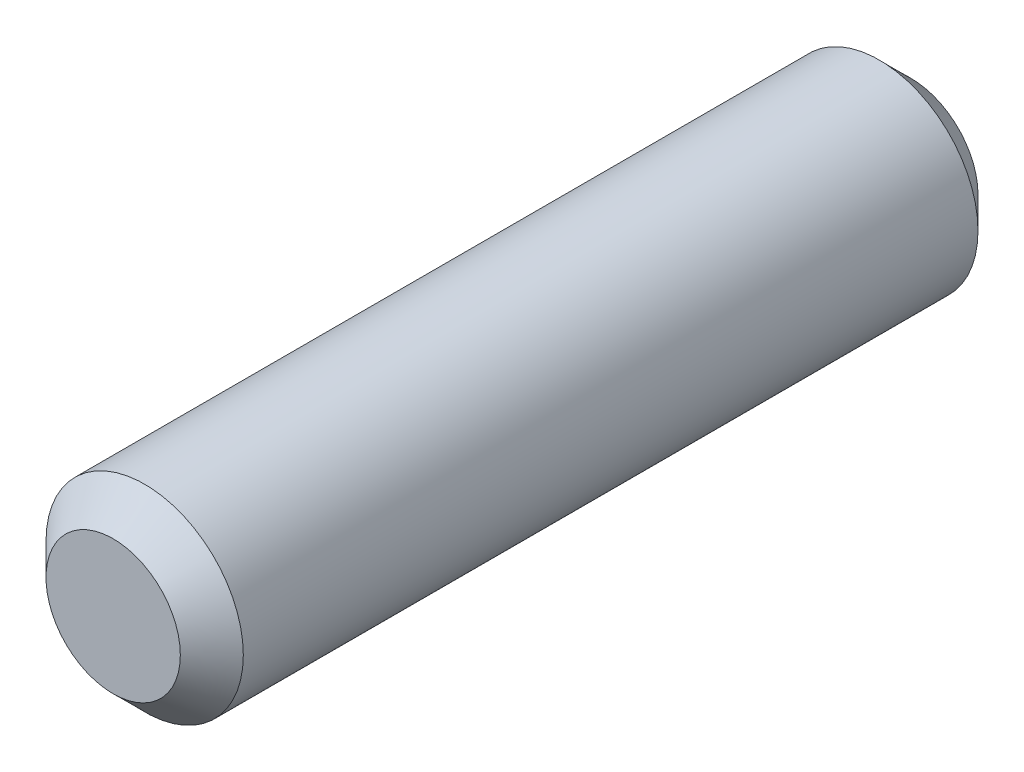
SolidWorks part; units mm, degrees
ref_plane "Front Plane" through (0, 0, 0) normal (0, 0, 1) x (1, 0, 0)
ref_plane "Top Plane" through (0, 0, 0) normal (0, 1, 0) x (1, 0, 0)
ref_plane "Right Plane" through (0, 0, 0) normal (1, 0, 0) x (0, 0, -1)
sketch "Sketch1" plane through (0, 0, 0) normal (0, 0, 1) x (1, 0, 0)
  circle A0 centre (0, 0) radius 2.35
extrude "Boss-Extrude1" add sketch "Sketch1" along normal blind 19 contours A0
fillet "Fillet1" radius 0.75 2 edges at (2.35, 0, 0) (2.35, 0, 19) profile chamfer
